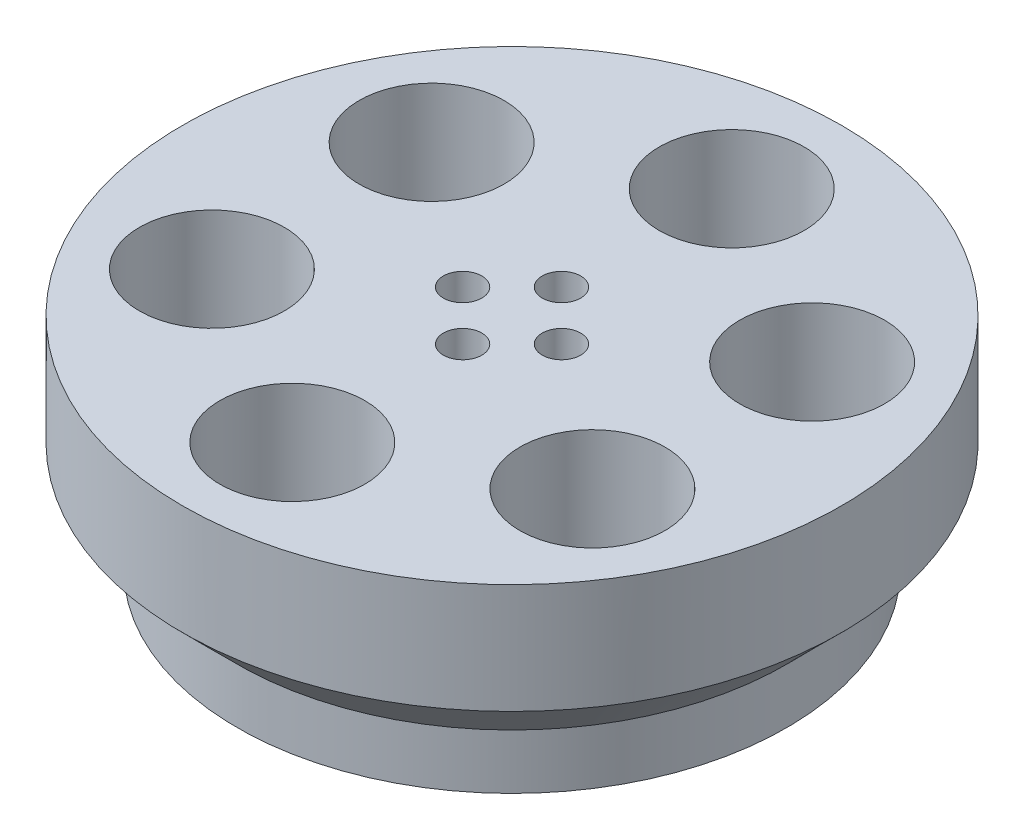
SolidWorks part; units mm, degrees
ref_plane "Front Plane" through (0, 0, 0) normal (0, 0, 1) x (1, 0, 0)
ref_plane "Top Plane" through (0, 0, 0) normal (0, 1, 0) x (1, 0, 0)
ref_plane "Right Plane" through (0, 0, 0) normal (1, 0, 0) x (0, 0, -1)
sketch "Sketch1" plane through (0, 0, 0) normal (0, 1, 0) x (1, 0, 0)
  circle A0 centre (0, 0) radius 30
  dimension "D1" = 60
extrude "Boss-Extrude1" add sketch "Sketch1" along normal blind 20
sketch "Sketch2" plane through (0, 20, 0) normal (0, 1, 0) x (1, 0, 0)
  line L0 (0, -14.85) -> (0, 14.85) construction
  line L1 (-14.85, 0) -> (14.85, 0) construction
  line L2 (0, 26.6) -> (16.0728, 26.6) construction
  line L3 (0, 30) -> (15.4299, 30) construction
  circle A0 centre (0, 20) radius 6.6
  circle A1 centre (0, 0) radius 30 construction
  dimension "D1" = 13.2
  dimension "D2" = 20
  dimension "D3" = 3.4
extrude "Cut-Extrude1" cut sketch "Sketch2" against normal blind 10
sketch "Sketch3" plane through (0, 10, 0) normal (0, 1, 0) x (1, 0, 0)
  circle A0 centre (0, 20) radius 2
  dimension "D1" = 4
extrude "Cut-Extrude2" cut sketch "Sketch3" against normal blind 35
pattern_circular "CirPattern1" count 6 over 360 about axis through (0, 0, 0) along (0, 1, 0) of "Cut-Extrude1", "Cut-Extrude2"
sketch "Sketch6" plane through (0, 20, 0) normal (0, 1, 0) x (1, 0, 0)
  circle A0 centre (4.5, 0) radius 1.75
  dimension "D2" = 3.5
  dimension "D1" = 4.5
extrude "Cut-Extrude4" cut sketch "Sketch6" against normal blind 45
pattern_circular "CirPattern3" count 4 over 360 about axis through (0, 0, 0) along (0, 1, 0) of "Cut-Extrude4"
sketch "Sketch7" plane through (0, 0, 0) normal (0, 0, 1) x (1, 0, 0)
  line L0 (-25, 0) -> (-25, 5)
  line L1 (-30, 0) -> (30, 0) construction
  line L2 (-25, 5) -> (-30, 10)
  line L3 (-30, 20) -> (-30, 0) construction
  line L4 (-25, 0) -> (-30, 0)
  line L5 (-30, 0) -> (-30, 10)
  line L6 (0, 0) -> (0, 26.2682) construction
  dimension "D1" = 5
  dimension "D2" = 10
  dimension "D3" = 5
revolve "Cut-Revolve1" cut sketch "Sketch7" angle 360 about L6
